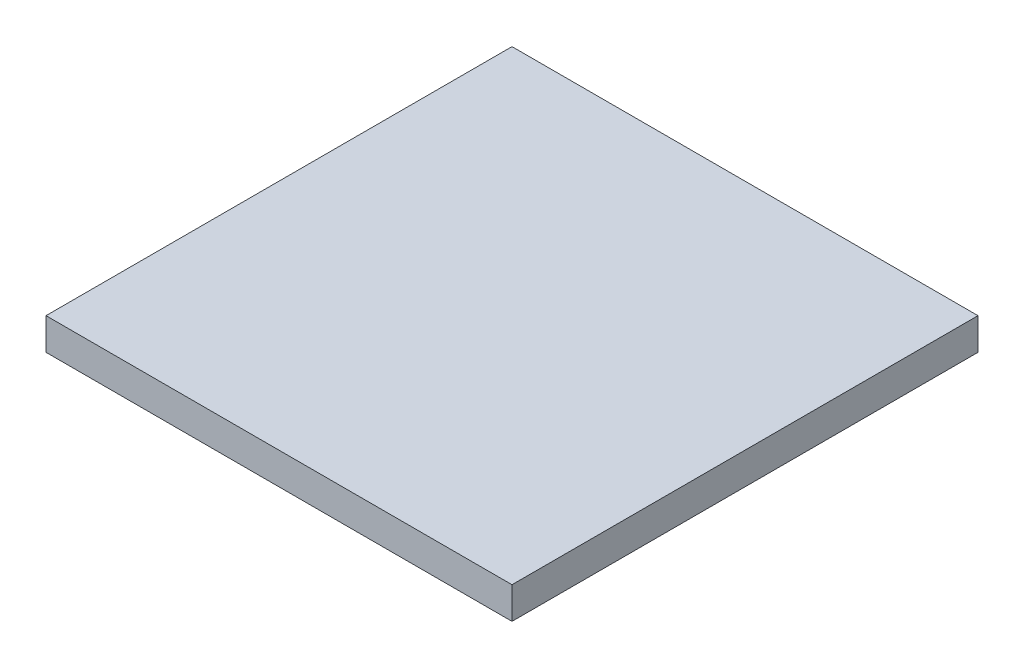
SolidWorks part; units mm, degrees
ref_plane "Plan de face" through (0, 0, 0) normal (0, 0, 1) x (1, 0, 0)
ref_plane "Plan de dessus" through (0, 0, 0) normal (0, 1, 0) x (1, 0, 0)
ref_plane "Plan de droite" through (0, 0, 0) normal (1, 0, 0) x (0, 0, -1)
sketch "Esquisse1" plane through (0, 0, 0) normal (0, 1, 0) x (1, 0, 0)
  line L1 (22, 22) -> (-22, 22)
  line L2 (22, 22) -> (22, -22)
  line L3 (22, -22) -> (-22, -22)
  line L4 (-22, 22) -> (-22, -22)
  line L5 (22, 22) -> (-22, -22) construction
  line L6 (22, -22) -> (-22, 22) construction
  point P0 (0, 0)
  dimension "D1" = 44
  dimension "D2" = 44
extrude "Boss.-Extru.1" add sketch "Esquisse1" along normal blind 3
